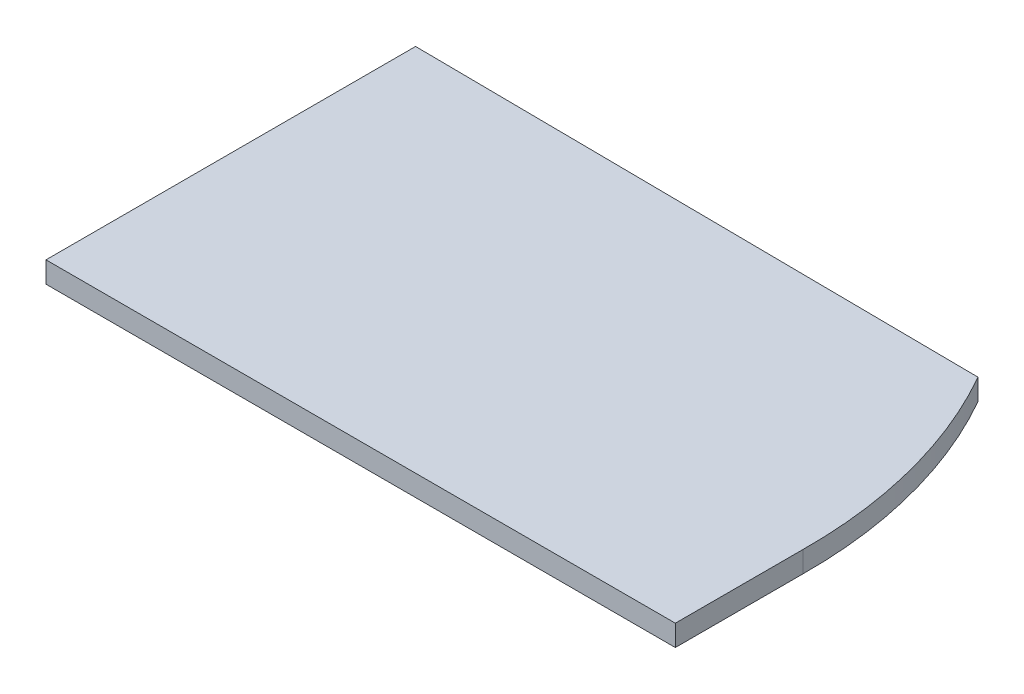
SolidWorks part; units mm, degrees
ref_plane "Front Plane" through (0, 0, 0) normal (0, 0, 1) x (1, 0, 0)
ref_plane "Top Plane" through (0, 0, 0) normal (0, 1, 0) x (1, 0, 0)
ref_plane "Right Plane" through (0, 0, 0) normal (1, 0, 0) x (0, 0, -1)
sketch "Sketch1" plane through (0, 0, 0) normal (0, 1, 0) x (1, 0, 0)
  line L0 (268.1932, 172.5395) -> (-12, 172.5395) construction
  line L1 (0, 0) -> (298, 0)
  line L2 (0, 0) -> (0, 175)
  line L4 (298, 0) -> (298, 60.4094)
  line L5 (0, 175) -> (268.7747, 172.5395)
  arc A0 (298, 60.4094) -> (268.7747, 172.5395) centre (75.7283, 62.3507) ccw
  arc A1 (296.7855, 84) -> (252.9805, 197) centre (68.28, 60.4094) ccw construction
extrude "Boss-Extrude1" add sketch "Sketch1" along normal blind 10
